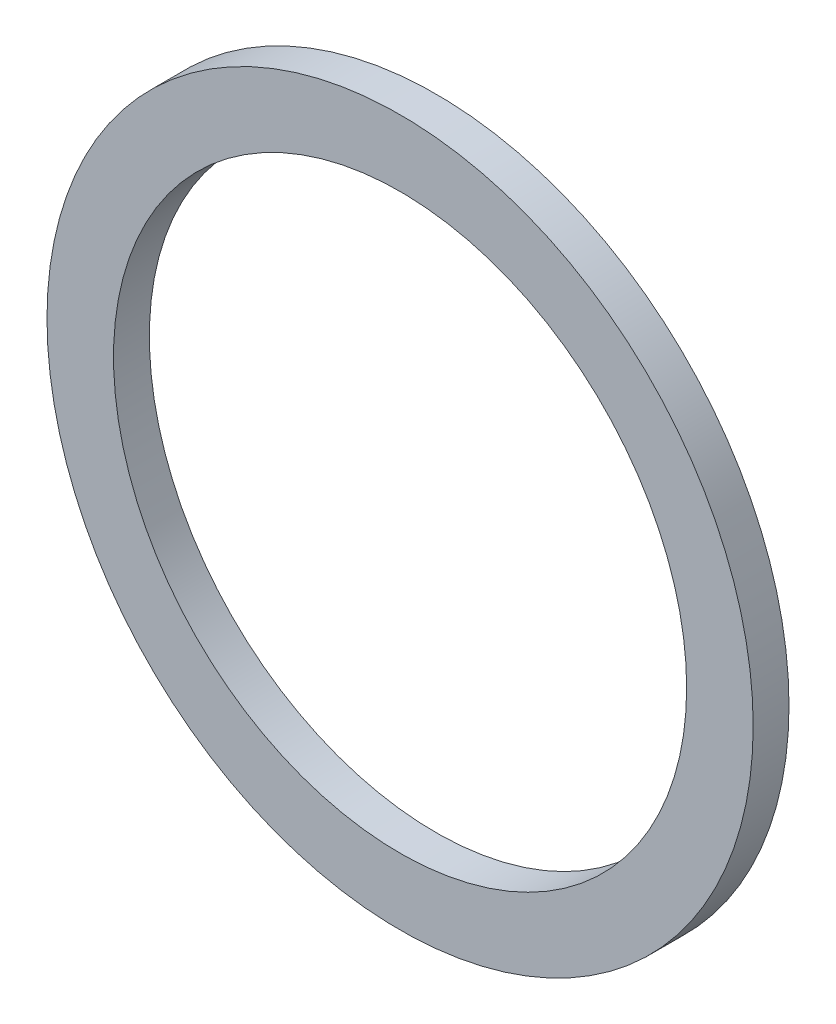
SolidWorks part; units mm, degrees
ref_plane "Płaszczyzna przednia" through (0, 0, 0) normal (0, 0, 1) x (1, 0, 0)
ref_plane "Płaszczyzna górna" through (0, 0, 0) normal (0, 1, 0) x (1, 0, 0)
ref_plane "Płaszczyzna prawa" through (0, 0, 0) normal (1, 0, 0) x (0, 0, -1)
sketch "Sketch1" plane through (0, 0, 0) normal (0, 0, 1) x (1, 0, 0)
  circle A0 centre (0, 0) radius 14
  circle A1 centre (0, 0) radius 17.25
  dimension "D1" = 28
  dimension "D2" = 34.5
extrude "Boss-Extrude1" add sketch "Sketch1" along normal blind 1.75
